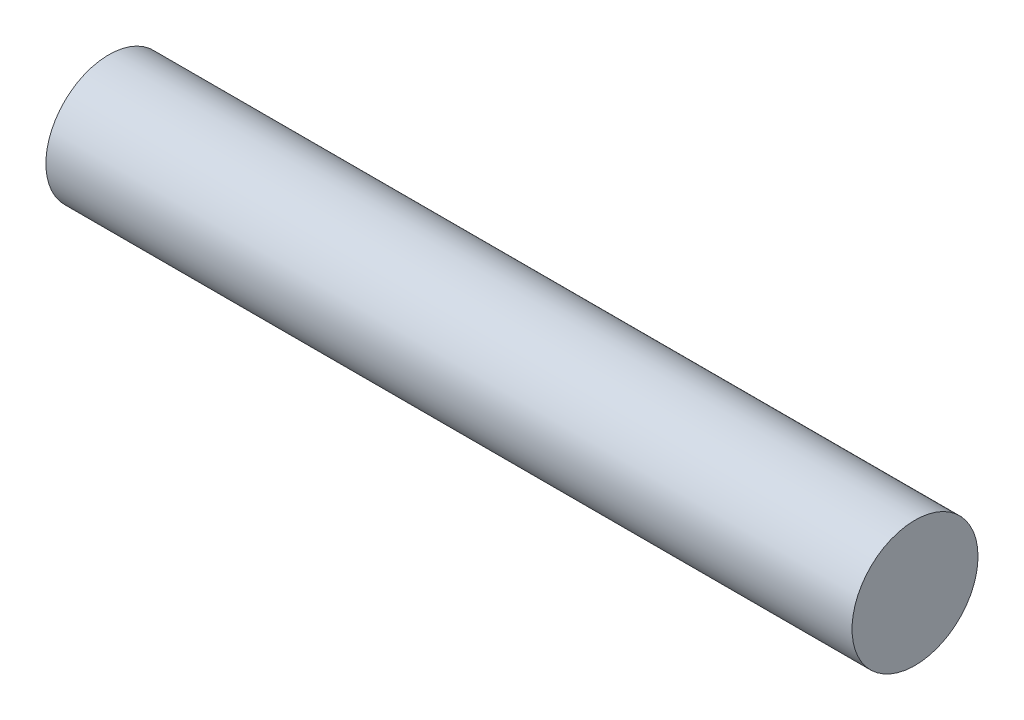
SolidWorks part; units mm, degrees
ref_plane "Front Plane" through (0, 0, 0) normal (0, 0, 1) x (1, 0, 0)
ref_plane "Top Plane" through (0, 0, 0) normal (0, 1, 0) x (1, 0, 0)
ref_plane "Right Plane" through (0, 0, 0) normal (1, 0, 0) x (0, 0, -1)
sketch "Sketch1" plane through (0, 0, 0) normal (1, 0, 0) x (0, 0, -1)
  line L5 (-9.525, 19.05) -> (9.525, -19.05) construction
  circle A0 centre (0, 0) radius 15.875
  point P0 (0, 0)
  dimension "D1" = 31.75
extrude "Boss-Extrude1" add sketch "Sketch1" along normal blind 203.2
